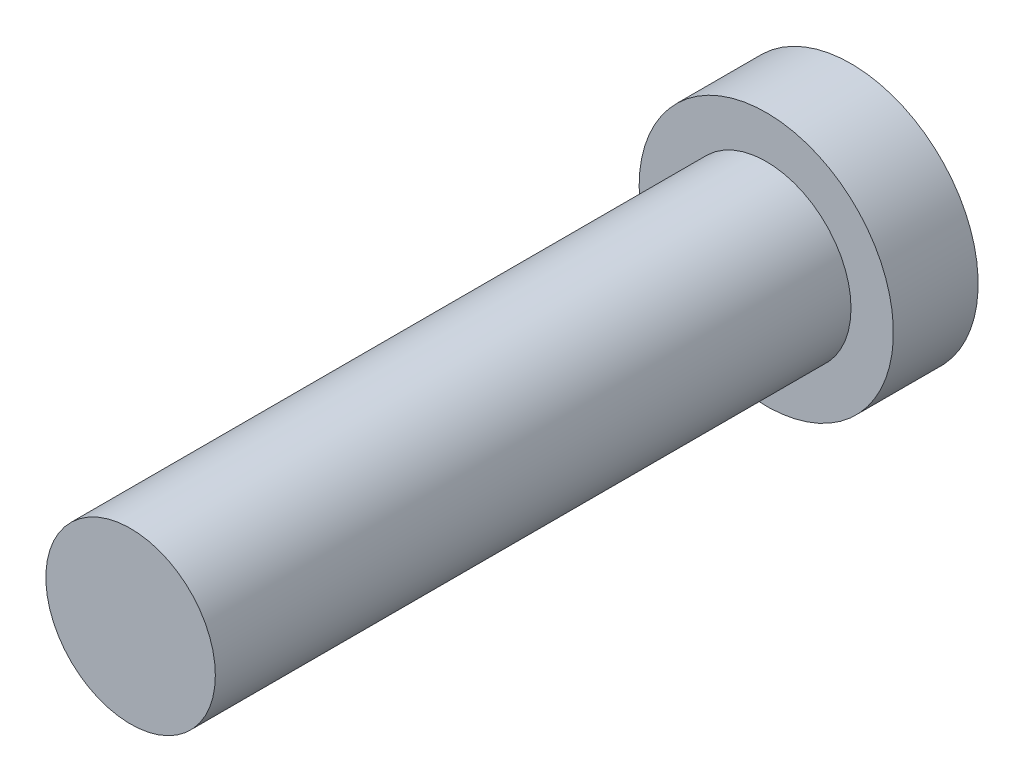
SolidWorks part; units mm, degrees
ref_plane "Front Plane" through (0, 0, 0) normal (0, 0, 1) x (1, 0, 0)
ref_plane "Top Plane" through (0, 0, 0) normal (0, 1, 0) x (1, 0, 0)
ref_plane "Right Plane" through (0, 0, 0) normal (1, 0, 0) x (0, 0, -1)
sketch "Sketch1" plane through (0, 0, 0) normal (0, 0, 1) x (1, 0, 0)
  circle A0 centre (0, 0) radius 10
  dimension "D1" = 20
extrude "Boss-Extrude1" add sketch "Sketch1" along normal blind 75
sketch "Sketch2" plane through (0, 0, 0) normal (0, 0, -1) x (-1, 0, 0)
  circle A0 centre (0, 0) radius 15
  dimension "D1" = 30
extrude "Boss-Extrude2" add sketch "Sketch2" along normal blind 10
